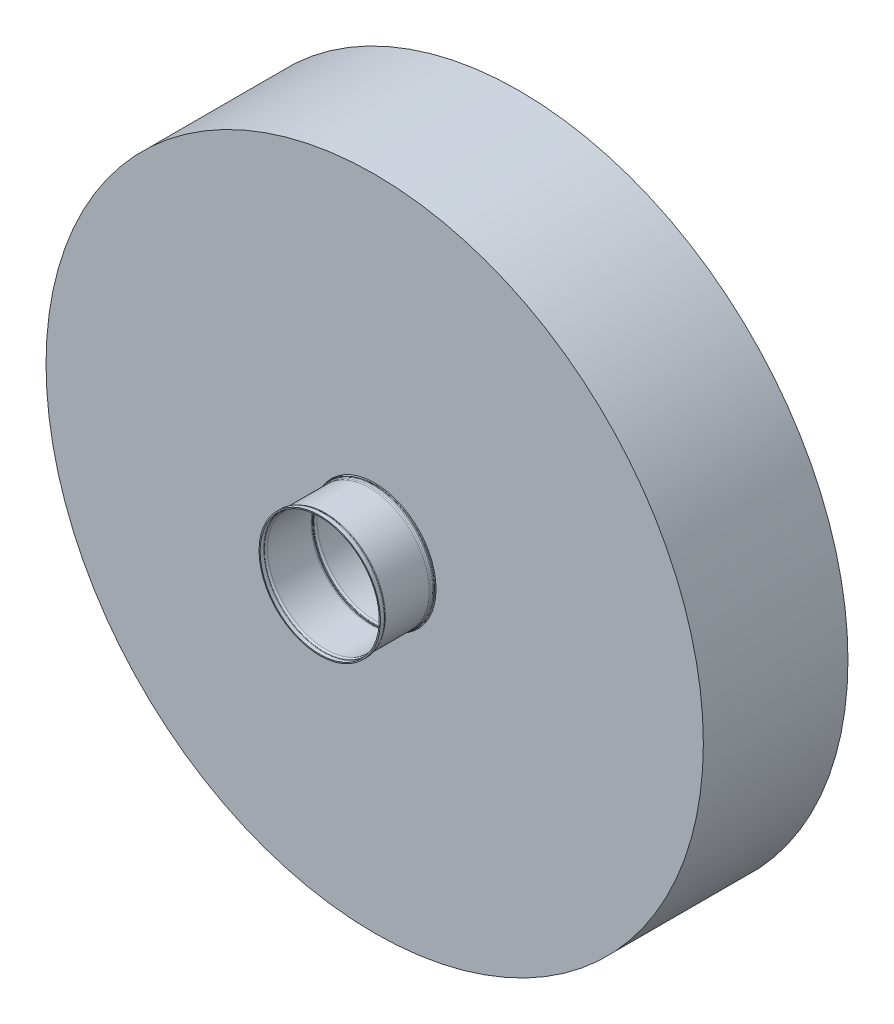
SolidWorks part; units mm, degrees
ref_plane "Front Plane" through (0, 0, 0) normal (0, 0, 1) x (1, 0, 0)
ref_plane "Top Plane" through (0, 0, 0) normal (0, 1, 0) x (1, 0, 0)
ref_plane "Right Plane" through (0, 0, 0) normal (1, 0, 0) x (0, 0, -1)
sketch "Sketch1" plane through (0, 0, 0) normal (0, 0, 1) x (1, 0, 0)
  circle A0 centre (0, 0) radius 28
  circle A1 centre (0, 0) radius 150
extrude "Boss-Extrude1" add sketch "Sketch1" along normal blind 66
sketch "Sketch3" plane through (0, 0, 0) normal (1, 0, 0) x (0, 0, -1)
  line L0 (0, 0) -> (-66, 0) construction
  line L1 (0, -28) -> (0, 28) construction
  line L2 (-66, 28) -> (-66, -28) construction
  line L3 (2.3314, 27.2) -> (22.2571, 27.2)
  line L4 (0, 27.2) -> (-66, 27.2) construction
  line L5 (-91.0885, 27.7) -> (25.0885, 27.7) construction
  line L6 (-91.0885, 27.7) -> (-89.4198, 27.7)
  line L7 (1.7343, 27.4657) -> (1.7657, 27.4343)
  line L8 (-88.8541, 27.4657) -> (-88.8228, 27.4343)
  line L9 (-66.2343, 27.4343) -> (-66.2657, 27.4657)
  line L10 (-33, 0) -> (-33, -3.4567) construction
  line L11 (-66.8314, 27.7) -> (-67.1686, 27.7)
  line L12 (-67.7343, 27.4657) -> (-67.7657, 27.4343)
  line L13 (-91.0885, 27.2) -> (25.0885, 27.2) construction
  line L14 (-65.6686, 27.2) -> (-0.3314, 27.2)
  line L15 (0.8314, 27.7) -> (1.1686, 27.7)
  line L16 (0.2343, 27.4343) -> (0.2657, 27.4657)
  line L17 (22.8541, 27.4657) -> (22.8228, 27.4343)
  line L18 (25.0885, 27.7) -> (23.4198, 27.7)
  line L19 (-91.0885, 27.2) -> (-89.4198, 27.2)
  line L20 (-89.2077, 27.1121) -> (-89.1763, 27.0808)
  line L21 (-88.2571, 26.7) -> (-68.3314, 26.7)
  line L22 (-67.3808, 27.1121) -> (-67.4121, 27.0808)
  line L23 (-66.8314, 27.2) -> (-67.1686, 27.2)
  line L24 (-66.5879, 27.0808) -> (-66.6192, 27.1121)
  line L25 (-65.6686, 26.7) -> (-0.3314, 26.7)
  line L26 (0.5879, 27.0808) -> (0.6192, 27.1121)
  line L27 (0.8314, 27.2) -> (1.1686, 27.2)
  line L28 (1.3808, 27.1121) -> (1.4121, 27.0808)
  line L29 (2.3314, 26.7) -> (22.2571, 26.7)
  line L30 (23.2077, 27.1121) -> (23.1763, 27.0808)
  line L31 (25.0885, 27.2) -> (23.4198, 27.2)
  line L32 (-91.0885, 27.7) -> (-91.0885, 27.2)
  line L33 (25.0885, 27.7) -> (25.0885, 27.2)
  line L43 (-88.2571, 27.2) -> (-68.3314, 27.2)
  arc A0 (22.8541, 27.4657) -> (23.4198, 27.7) centre (23.4198, 26.9) cw
  arc A1 (22.2571, 27.2) -> (22.8228, 27.4343) centre (22.2571, 28) ccw
  arc A2 (0.8314, 27.7) -> (0.2657, 27.4657) centre (0.8314, 26.9) ccw
  arc A3 (1.7343, 27.4657) -> (1.1686, 27.7) centre (1.1686, 26.9) ccw
  arc A4 (0.2343, 27.4343) -> (-0.3314, 27.2) centre (-0.3314, 28) cw
  arc A5 (2.3314, 27.2) -> (1.7657, 27.4343) centre (2.3314, 28) cw
  arc A6 (-67.1686, 27.7) -> (-67.7343, 27.4657) centre (-67.1686, 26.9) ccw
  arc A7 (-66.2657, 27.4657) -> (-66.8314, 27.7) centre (-66.8314, 26.9) ccw
  arc A8 (-67.7657, 27.4343) -> (-68.3314, 27.2) centre (-68.3314, 28) cw
  arc A9 (-66.2343, 27.4343) -> (-65.6686, 27.2) centre (-65.6686, 28) ccw
  arc A10 (-88.8228, 27.4343) -> (-88.2571, 27.2) centre (-88.2571, 28) ccw
  arc A11 (-89.4198, 27.7) -> (-88.8541, 27.4657) centre (-89.4198, 26.9) cw
  arc A12 (-89.4198, 27.2) -> (-89.2077, 27.1121) centre (-89.4198, 26.9) cw
  arc A13 (-89.1763, 27.0808) -> (-88.2571, 26.7) centre (-88.2571, 28) ccw
  arc A14 (-67.4121, 27.0808) -> (-68.3314, 26.7) centre (-68.3314, 28) cw
  arc A15 (-67.1686, 27.2) -> (-67.3808, 27.1121) centre (-67.1686, 26.9) ccw
  arc A16 (-66.6192, 27.1121) -> (-66.8314, 27.2) centre (-66.8314, 26.9) ccw
  arc A17 (-66.5879, 27.0808) -> (-65.6686, 26.7) centre (-65.6686, 28) ccw
  arc A18 (0.5879, 27.0808) -> (-0.3314, 26.7) centre (-0.3314, 28) cw
  arc A19 (0.8314, 27.2) -> (0.6192, 27.1121) centre (0.8314, 26.9) ccw
  arc A20 (1.3808, 27.1121) -> (1.1686, 27.2) centre (1.1686, 26.9) ccw
  arc A21 (2.3314, 26.7) -> (1.4121, 27.0808) centre (2.3314, 28) cw
  arc A22 (22.2571, 26.7) -> (23.1763, 27.0808) centre (22.2571, 28) ccw
  arc A23 (23.2077, 27.1121) -> (23.4198, 27.2) centre (23.4198, 26.9) cw
  point P25 (23.0885, 27.7)
  point P29 (22.5885, 27.2)
  point P32 (0.5, 27.7)
  point P35 (1.5, 27.7)
  point P41 (2, 27.2)
  point P44 (-67.5, 27.7)
  point P47 (-66.5, 27.7)
  point P50 (-68, 27.2)
  point P56 (-88.5885, 27.2)
  point P59 (-89.0885, 27.7)
  dimension "D2" = 27.2
  dimension "D3" = 0.8
  dimension "D1" = 0.5
  dimension "D4" = 0.5
revolve "Revolve1" add sketch "Sketch3" angle 360 about L0
sketch "Sketch5" plane through (0, 0, 0) normal (0, 0, 1) x (1, 0, 0)
  line L0 (-28, 0) -> (-50, 0) construction
  line L1 (0.3052, -37.7766) -> (-0.3052, -37.7766)
  line L2 (28.3267, -69.2412) -> (28.3267, -49.2412) construction
  line L3 (-21.9576, -30.7413) -> (-22.4514, -30.3825)
  line L4 (22.4514, -30.3825) -> (21.9576, -30.7413)
  line L5 (39.6017, -35.6122) -> (39.6017, -64.2412)
  line L6 (-39.6017, -35.6122) -> (-39.6017, -64.2412)
  line L7 (12.0517, -45.1412) -> (12.0517, -49.2412) construction
  line L8 (-12.0517, -45.1412) -> (-12.0517, -49.2412) construction
  line L9 (12.0517, -49.2412) -> (-12.0517, -49.2412)
  line L10 (-17.0517, -54.2412) -> (-17.0517, -64.2412)
  line L11 (17.0517, -54.2412) -> (17.0517, -64.2412)
  line L12 (-22.0517, -69.2412) -> (-34.6017, -69.2412)
  line L13 (22.0517, -69.2412) -> (34.6017, -69.2412)
  line L14 (37.6017, -35.6122) -> (37.6017, -64.2412)
  line L15 (22.0517, -67.2412) -> (34.6017, -67.2412)
  line L16 (19.0517, -54.2412) -> (19.0517, -64.2412)
  line L17 (12.0517, -47.2412) -> (-12.0517, -47.2412)
  line L18 (-19.0517, -54.2412) -> (-19.0517, -64.2412)
  line L19 (-22.0517, -67.2412) -> (-34.6017, -67.2412)
  line L20 (-37.6017, -35.6122) -> (-37.6017, -64.2412)
  line L21 (-23.1332, -32.3593) -> (-23.627, -32.0005)
  line L22 (0.3052, -39.7766) -> (-0.3052, -39.7766)
  line L23 (23.627, -32.0005) -> (23.1332, -32.3593)
  line L24 (-28.3267, -69.2412) -> (-28.3267, -49.2412) construction
  line L25 (19.1517, -46.4507) -> (19.1517, -64.2412)
  line L26 (22.0517, -67.1412) -> (26.2767, -67.1412)
  line L27 (28.3767, -53.9226) -> (28.3767, -52.2412)
  line L28 (28.3767, -65.1412) -> (28.3767, -64.5598)
  line L29 (28.2767, -53.9226) -> (28.2767, -52.2412)
  line L30 (34.6017, -67.1412) -> (30.3767, -67.1412)
  line L31 (37.5017, -54.2412) -> (37.5017, -64.2412)
  line L33 (28.2767, -65.1412) -> (28.2767, -64.5598)
  line L35 (27.9406, -50.8616) -> (23.8467, -42.956)
  line L36 (31.3767, -49.2412) -> (32.5017, -49.2412)
  line L38 (26.1647, -51.7814) -> (22.0707, -43.8757)
  line L39 (21.1517, -46.4507) -> (21.1517, -64.2412)
  line L40 (22.0517, -65.1412) -> (26.2767, -65.1412)
  line L41 (26.2767, -65.1412) -> (26.2767, -64.5598)
  line L42 (26.2767, -53.9226) -> (26.2767, -52.2412)
  line L43 (31.3767, -51.2412) -> (32.5017, -51.2412)
  line L44 (35.5017, -54.2412) -> (35.5017, -64.2412)
  line L45 (34.6017, -65.1412) -> (30.3767, -65.1412)
  line L46 (30.3767, -65.1412) -> (30.3767, -64.5598)
  line L47 (30.3767, -53.9226) -> (30.3767, -52.2412)
  line L48 (0, -49.2412) -> (0, -54.6682) construction
  line L49 (-31.3767, -49.2412) -> (-32.5017, -49.2412)
  line L50 (-28.3767, -53.9226) -> (-28.3767, -52.2412)
  line L51 (-28.3767, -65.1412) -> (-28.3767, -64.5598)
  line L52 (-34.6017, -67.1412) -> (-30.3767, -67.1412)
  line L53 (-37.5017, -54.2412) -> (-37.5017, -64.2412)
  line L54 (-31.3767, -51.2412) -> (-32.5017, -51.2412)
  line L55 (-30.3767, -53.9226) -> (-30.3767, -52.2412)
  line L56 (-30.3767, -65.1412) -> (-30.3767, -64.5598)
  line L57 (-34.6017, -65.1412) -> (-30.3767, -65.1412)
  line L58 (-35.5017, -54.2412) -> (-35.5017, -64.2412)
  line L59 (-26.1647, -51.7814) -> (-22.0707, -43.8757)
  line L60 (-26.2767, -53.9226) -> (-26.2767, -52.2412)
  line L61 (-26.2767, -65.1412) -> (-26.2767, -64.5598)
  line L62 (-22.0517, -65.1412) -> (-26.2767, -65.1412)
  line L63 (-21.1517, -46.4507) -> (-21.1517, -64.2412)
  line L64 (-27.9406, -50.8616) -> (-23.8467, -42.956)
  line L65 (-28.2767, -53.9226) -> (-28.2767, -52.2412)
  line L66 (-28.2767, -65.1412) -> (-28.2767, -64.5598)
  line L67 (-22.0517, -67.1412) -> (-26.2767, -67.1412)
  line L68 (-19.1517, -46.4507) -> (-19.1517, -64.2412)
  arc A0 (25.5034, -28.1599) -> (23.5717, -23.4899) centre (31.5517, -22.9236) ccw
  circle A1 centre (0, 0) radius 24.2 construction
  arc A2 (15.0561, -29.6768) -> (5.2629, -32.8588) centre (12.0517, -37.0912) ccw
  circle A3 centre (-39, 0) radius 11 construction
  circle A4 centre (-31.5517, 22.9236) radius 11 construction
  circle A5 centre (-12.0517, 37.0912) radius 11 construction
  circle A6 centre (12.0517, 37.0912) radius 11 construction
  circle A7 centre (31.5517, 22.9236) radius 11 construction
  circle A8 centre (39, 0) radius 11 construction
  circle A9 centre (31.5517, -22.9236) radius 11 construction
  circle A10 centre (12.0517, -37.0912) radius 11 construction
  circle A11 centre (-12.0517, -37.0912) radius 11 construction
  circle A12 centre (-31.5517, -22.9236) radius 11 construction
  circle A13 centre (31.5517, -22.9236) radius 4
  circle A14 centre (12.0517, -37.0912) radius 4
  circle A15 centre (-12.0517, -37.0912) radius 4
  circle A16 centre (-31.5517, -22.9236) radius 4
  arc A17 (-5.2629, -32.8588) -> (-15.0561, -29.6768) centre (-12.0517, -37.0912) ccw
  arc A18 (-23.5717, -23.4899) -> (-25.5034, -28.1599) centre (-31.5517, -22.9236) ccw
  arc A19 (-22.7286, -27.9179) -> (-19.528, -30.2433) centre (0, 0) ccw
  arc A20 (-22.9253, -25.1084) -> (-16.7952, -29.5622) centre (0, 0) ccw
  arc A21 (4.8058, -40.5983) -> (19.9751, -35.6695) centre (12.0517, -37.0912) ccw
  arc A22 (-19.9751, -35.6695) -> (-4.8058, -40.5983) centre (-12.0517, -37.0912) ccw
  arc A23 (-33.4331, -30.7507) -> (-27.751, -30.0199) centre (-31.5517, -22.9236) ccw
  arc A24 (19.528, -30.2433) -> (22.7286, -27.9179) centre (0, 0) ccw
  arc A25 (4.0807, -37.7723) -> (18.9006, -32.957) centre (12.0517, -37.0912) ccw
  arc A26 (16.7952, -29.5622) -> (22.9253, -25.1084) centre (0, 0) ccw
  arc A27 (27.751, -30.0199) -> (33.4331, -30.7507) centre (31.5517, -22.9236) ccw
  arc A28 (-3.7886, -33.7883) -> (3.7886, -33.7883) centre (0, 0) ccw
  arc A29 (-1.9781, -35.9456) -> (1.9781, -35.9456) centre (0, 0) ccw
  arc A31 (-18.9006, -32.957) -> (-4.0807, -37.7723) centre (-12.0517, -37.0912) ccw
  arc A32 (-27.751, -30.0199) -> (-22.4514, -30.3825) centre (-25.3904, -34.4276) cw
  arc A33 (-22.7286, -27.9179) -> (-25.5034, -28.1599) centre (-23.9913, -29.4689) ccw
  arc A34 (-22.9253, -25.1084) -> (-23.5717, -23.4899) centre (-21.5767, -23.6314) cw
  arc A35 (-18.9006, -32.957) -> (-19.528, -30.2433) centre (-20.6129, -31.9235) ccw
  arc A36 (-16.7952, -29.5622) -> (-15.0561, -29.6768) centre (-15.8072, -27.8232) ccw
  arc A37 (-1.9781, -35.9456) -> (-4.0807, -37.7723) centre (-2.088, -37.9426) ccw
  arc A38 (-3.7886, -33.7883) -> (-5.2629, -32.8588) centre (-3.5657, -31.8007) cw
  arc A39 (4.0807, -37.7723) -> (1.9781, -35.9456) centre (2.088, -37.9426) ccw
  arc A40 (5.2629, -32.8588) -> (3.7886, -33.7883) centre (3.5657, -31.8007) cw
  arc A41 (15.0561, -29.6768) -> (16.7952, -29.5622) centre (15.8072, -27.8232) ccw
  arc A42 (18.9006, -32.957) -> (19.528, -30.2433) centre (20.6129, -31.9235) cw
  arc A43 (22.7286, -27.9179) -> (25.5034, -28.1599) centre (23.9913, -29.4689) cw
  arc A44 (23.5717, -23.4899) -> (22.9253, -25.1084) centre (21.5767, -23.6314) cw
  arc A46 (-19.9751, -35.6695) -> (-21.9576, -30.7413) centre (-24.8965, -34.7864) ccw
  arc A47 (-4.8058, -40.5983) -> (-0.3052, -37.7766) centre (-0.3052, -42.7766) cw
  arc A49 (4.8058, -40.5983) -> (0.3052, -37.7766) centre (0.3052, -42.7766) ccw
  arc A50 (19.9751, -35.6695) -> (21.9576, -30.7413) centre (24.8965, -34.7864) cw
  arc A52 (27.751, -30.0199) -> (22.4514, -30.3825) centre (25.3904, -34.4276) ccw
  arc A53 (-39.6017, -35.6122) -> (-33.4331, -30.7507) centre (-34.6017, -35.6122) cw
  arc A54 (39.6017, -35.6122) -> (33.4331, -30.7507) centre (34.6017, -35.6122) ccw
  arc A55 (12.0517, -49.2412) -> (17.0517, -54.2412) centre (12.0517, -54.2412) cw
  arc A56 (-12.0517, -49.2412) -> (-17.0517, -54.2412) centre (-12.0517, -54.2412) ccw
  arc A57 (34.6017, -69.2412) -> (39.6017, -64.2412) centre (34.6017, -64.2412) ccw
  arc A58 (-34.6017, -69.2412) -> (-39.6017, -64.2412) centre (-34.6017, -64.2412) cw
  arc A59 (-22.0517, -69.2412) -> (-17.0517, -64.2412) centre (-22.0517, -64.2412) ccw
  arc A60 (17.0517, -64.2412) -> (22.0517, -69.2412) centre (22.0517, -64.2412) ccw
  arc A61 (34.6017, -67.2412) -> (37.6017, -64.2412) centre (34.6017, -64.2412) ccw
  arc A62 (19.0517, -64.2412) -> (22.0517, -67.2412) centre (22.0517, -64.2412) ccw
  arc A63 (12.0517, -47.2412) -> (19.0517, -54.2412) centre (12.0517, -54.2412) cw
  arc A64 (-12.0517, -47.2412) -> (-19.0517, -54.2412) centre (-12.0517, -54.2412) ccw
  arc A65 (-22.0517, -67.2412) -> (-19.0517, -64.2412) centre (-22.0517, -64.2412) ccw
  arc A66 (-34.6017, -67.2412) -> (-37.6017, -64.2412) centre (-34.6017, -64.2412) cw
  arc A67 (-37.6017, -35.6122) -> (-33.9005, -32.6953) centre (-34.6017, -35.6122) cw
  arc A68 (-33.9005, -32.6953) -> (-26.8068, -31.783) centre (-31.5517, -22.9236) ccw
  arc A69 (-26.8068, -31.783) -> (-23.627, -32.0005) centre (-25.3904, -34.4276) cw
  arc A70 (-21.9437, -35.3162) -> (-23.1332, -32.3593) centre (-24.8965, -34.7864) ccw
  arc A71 (-21.9437, -35.3162) -> (-3.0055, -41.4696) centre (-12.0517, -37.0912) ccw
  arc A72 (-3.0055, -41.4696) -> (-0.3052, -39.7766) centre (-0.3052, -42.7766) cw
  arc A73 (3.0055, -41.4696) -> (0.3052, -39.7766) centre (0.3052, -42.7766) ccw
  arc A74 (3.0055, -41.4696) -> (21.9437, -35.3162) centre (12.0517, -37.0912) ccw
  arc A75 (21.9437, -35.3162) -> (23.1332, -32.3593) centre (24.8965, -34.7864) cw
  arc A76 (26.8068, -31.783) -> (23.627, -32.0005) centre (25.3904, -34.4276) ccw
  arc A77 (26.8068, -31.783) -> (33.9005, -32.6953) centre (31.5517, -22.9236) ccw
  arc A78 (37.6017, -35.6122) -> (33.9005, -32.6953) centre (34.6017, -35.6122) ccw
  circle A79 centre (28.3267, -59.2412) radius 1.6
  circle A80 centre (-28.3267, -59.2412) radius 1.6
  circle A81 centre (28.3267, -59.2412) radius 3.6
  circle A82 centre (-28.3267, -59.2412) radius 3.6
  arc A83 (19.1517, -64.2412) -> (22.0517, -67.1412) centre (22.0517, -64.2412) ccw
  arc A84 (29.6574, -55.7888) -> (28.3767, -53.9226) centre (30.3767, -53.9226) cw
  arc A85 (26.996, -55.7888) -> (26.996, -62.6936) centre (28.3267, -59.2412) ccw
  arc A87 (28.2767, -64.5598) -> (26.996, -62.6936) centre (26.2767, -64.5598) ccw
  arc A88 (26.996, -55.7888) -> (28.2767, -53.9226) centre (26.2767, -53.9226) ccw
  arc A89 (26.2767, -67.1412) -> (28.2767, -65.1412) centre (26.2767, -65.1412) ccw
  arc A91 (29.6574, -55.7888) -> (29.6574, -62.6936) centre (28.3267, -59.2412) cw
  arc A92 (28.3767, -64.5598) -> (29.6574, -62.6936) centre (30.3767, -64.5598) cw
  arc A93 (30.3767, -67.1412) -> (28.3767, -65.1412) centre (30.3767, -65.1412) cw
  arc A94 (37.5017, -64.2412) -> (34.6017, -67.1412) centre (34.6017, -64.2412) cw
  arc A95 (32.5017, -49.2412) -> (37.5017, -54.2412) centre (32.5017, -54.2412) cw
  arc A96 (20.2697, -42.9627) -> (20.4146, -42.7543) centre (12.0517, -37.0912) ccw
  arc A97 (27.9406, -50.8616) -> (28.2767, -52.2412) centre (25.2767, -52.2412) cw
  arc A98 (28.3767, -52.2412) -> (31.3767, -49.2412) centre (31.3767, -52.2412) cw
  arc A99 (19.1517, -46.4507) -> (20.2697, -42.9627) centre (25.1517, -46.4507) cw
  arc A100 (23.8467, -42.956) -> (20.4146, -42.7543) centre (22.0707, -43.8757) ccw
  arc A102 (21.897, -44.1254) -> (22.0707, -43.8757) centre (12.0517, -37.0912) ccw
  arc A103 (21.1517, -46.4507) -> (21.897, -44.1254) centre (25.1517, -46.4507) cw
  arc A104 (21.1517, -64.2412) -> (22.0517, -65.1412) centre (22.0517, -64.2412) ccw
  arc A107 (26.2767, -53.9226) -> (26.2767, -64.5598) centre (28.3267, -59.2412) ccw
  arc A109 (26.1647, -51.7814) -> (26.2767, -52.2412) centre (25.2767, -52.2412) cw
  arc A110 (30.3767, -52.2412) -> (31.3767, -51.2412) centre (31.3767, -52.2412) cw
  arc A111 (32.5017, -51.2412) -> (35.5017, -54.2412) centre (32.5017, -54.2412) cw
  arc A112 (35.5017, -64.2412) -> (34.6017, -65.1412) centre (34.6017, -64.2412) cw
  arc A115 (30.3767, -53.9226) -> (30.3767, -64.5598) centre (28.3267, -59.2412) cw
  arc A117 (-28.3767, -52.2412) -> (-31.3767, -49.2412) centre (-31.3767, -52.2412) ccw
  arc A118 (-29.6574, -55.7888) -> (-28.3767, -53.9226) centre (-30.3767, -53.9226) ccw
  arc A119 (-29.6574, -55.7888) -> (-29.6574, -62.6936) centre (-28.3267, -59.2412) ccw
  arc A120 (-28.3767, -64.5598) -> (-29.6574, -62.6936) centre (-30.3767, -64.5598) ccw
  arc A121 (-30.3767, -67.1412) -> (-28.3767, -65.1412) centre (-30.3767, -65.1412) ccw
  arc A122 (-37.5017, -64.2412) -> (-34.6017, -67.1412) centre (-34.6017, -64.2412) ccw
  arc A123 (-32.5017, -49.2412) -> (-37.5017, -54.2412) centre (-32.5017, -54.2412) ccw
  arc A124 (-30.3767, -52.2412) -> (-31.3767, -51.2412) centre (-31.3767, -52.2412) ccw
  arc A125 (-30.3767, -53.9226) -> (-30.3767, -64.5598) centre (-28.3267, -59.2412) ccw
  arc A126 (-35.5017, -64.2412) -> (-34.6017, -65.1412) centre (-34.6017, -64.2412) ccw
  arc A127 (-32.5017, -51.2412) -> (-35.5017, -54.2412) centre (-32.5017, -54.2412) ccw
  arc A128 (-21.1517, -46.4507) -> (-21.897, -44.1254) centre (-25.1517, -46.4507) ccw
  arc A129 (-21.897, -44.1254) -> (-22.0707, -43.8757) centre (-12.0517, -37.0912) cw
  arc A130 (-26.1647, -51.7814) -> (-26.2767, -52.2412) centre (-25.2767, -52.2412) ccw
  arc A131 (-26.2767, -53.9226) -> (-26.2767, -64.5598) centre (-28.3267, -59.2412) cw
  arc A132 (-21.1517, -64.2412) -> (-22.0517, -65.1412) centre (-22.0517, -64.2412) cw
  arc A133 (-19.1517, -46.4507) -> (-20.2697, -42.9627) centre (-25.1517, -46.4507) ccw
  arc A134 (-20.2697, -42.9627) -> (-20.4146, -42.7543) centre (-12.0517, -37.0912) cw
  arc A135 (-23.8467, -42.956) -> (-20.4146, -42.7543) centre (-22.0707, -43.8757) cw
  arc A136 (-27.9406, -50.8616) -> (-28.2767, -52.2412) centre (-25.2767, -52.2412) ccw
  arc A137 (-26.996, -55.7888) -> (-28.2767, -53.9226) centre (-26.2767, -53.9226) cw
  arc A138 (-26.996, -55.7888) -> (-26.996, -62.6936) centre (-28.3267, -59.2412) cw
  arc A139 (-28.2767, -64.5598) -> (-26.996, -62.6936) centre (-26.2767, -64.5598) cw
  arc A140 (-26.2767, -67.1412) -> (-28.2767, -65.1412) centre (-26.2767, -65.1412) cw
  arc A141 (-19.1517, -64.2412) -> (-22.0517, -67.1412) centre (-22.0517, -64.2412) cw
  point P32 (0, 0)
  point P63 (-6.2036, -42.5502)
  point P70 (19.9915, -38.0702)
  point P73 (15.8772, -30.0652)
  point P76 (-8.3998, -44.2091)
  point P77 (17.65, -31.3764)
  point P79 (-5.47, -32.5435)
  point P81 (16.84, -30.6825)
  point P116 (-39.6017, -22.9236)
  point P118 (14.7033, -29.5434)
  point P120 (39.6017, -22.9236)
  point P121 (19.1898, -40.7032)
  point P215 (28.2767, -55.5415)
  point P237 (28.2767, -49.2412)
  point P240 (28.3767, -49.2412)
extrude "Boss-Extrude4" add sketch "Sketch5" against normal blind 4 from offset 4 separate body contours L11 A60 L13 A57 L5 A54 A27 A52 L4 A50 A21 A49 L1 A47 A22 A46 L3 A32 A23 A53 L6 A58 L12 A59 L10 A56 L9 A55 A78 L14 A61 L15 A62 L16 A63 L17 A64 L18 A65 L19 A66 L20 A67 A68 A69 L21 A70 A71 A72 L22 | A0 A44 A26 A41 A2 A40 A28 A38 A17 A36 A20 A34 A18 A33 A19 A35 A31 A37 A29 A39 A25 A42 A24 A43 A13 A14 A15 A16 | L35 A100 A96 A99 L25 A83 L26 A89 L33 A87 A85 A88 L29 A97 L38 A109 L42 A107 L41 L40 A104 L39 A103 A102 | A98 L27 A84 A91 A92 L28 A93 L30 A94 L31 A95 L36 A115 L47 A110 L43 A111 L44 A112 L45 L46 | A141 L68 A133 A134 A135 L64 A136 L65 A137 A138 A139 L66 A140 L67 L63 A132 L62 L61 A131 L60 A130 L59 A129 A128 | L49 A123 L53 A122 L52 A121 L51 A120 A119 A118 L50 A117 A127 L54 A124 L55 A125 L56 L57 A126 L58 | A81 A79 | A82 A80 offset against normal yes
sketch "Sketch6" plane through (0, 0, -8) normal (0, 0, -1) x (-1, 0, 0)
  line L0 (-36.6017, -49.2412) -> (36.6017, -49.2412)
  line L1 (-39.6017, -35.6122) -> (-39.6017, -64.2412) construction
  line L2 (21.9576, -30.7413) -> (22.4514, -30.3825) construction
  line L3 (-39.6017, -35.6636) -> (-39.6017, -46.2412)
  line L4 (39.6017, -35.6122) -> (39.6017, -64.2412) construction
  line L5 (39.6017, -35.6636) -> (39.6017, -46.2412)
  line L6 (-0.3052, -37.7766) -> (0.3052, -37.7766) construction
  line L7 (-22.4514, -30.3825) -> (-21.9576, -30.7413) construction
  line L8 (21.9576, -30.7413) -> (22.4514, -30.3825)
  line L9 (-0.3052, -37.7766) -> (0.3052, -37.7766)
  line L10 (-22.4514, -30.3825) -> (-21.9576, -30.7413)
  line L11 (-23.627, -32.0005) -> (-23.1332, -32.3593)
  line L12 (-0.3052, -39.7766) -> (0.3052, -39.7766)
  line L13 (23.1332, -32.3593) -> (23.627, -32.0005)
  line L14 (37.6017, -35.6636) -> (37.6017, -46.2412)
  line L15 (-36.6017, -47.2412) -> (36.6017, -47.2412)
  line L16 (-37.6017, -35.6636) -> (-37.6017, -46.2412)
  circle A0 centre (31.5517, -22.9236) radius 4 construction
  circle A1 centre (12.0517, -37.0912) radius 4 construction
  circle A2 centre (-31.5517, -22.9236) radius 4 construction
  circle A3 centre (-12.0517, -37.0912) radius 4 construction
  circle A4 centre (31.5517, -22.9236) radius 4
  circle A5 centre (12.0517, -37.0912) radius 4
  circle A6 centre (-31.5517, -22.9236) radius 4
  circle A7 centre (-12.0517, -37.0912) radius 4
  arc A8 (-33.4375, -30.801) -> (-27.2468, -29.785) centre (-31.5517, -22.9236) ccw
  arc A9 (-37.6017, -35.6636) -> (-33.9032, -32.7461) centre (-34.6017, -35.6636) cw
  arc A10 (-33.9032, -32.7461) -> (-26.3657, -31.5905) centre (-31.5517, -22.9236) ccw
  arc A11 (-23.627, -32.0005) -> (-26.3657, -31.5905) centre (-25.3904, -34.4276) ccw
  arc A12 (-19.9075, -35.1174) -> (-4.536, -40.1119) centre (-12.0517, -37.0912) ccw
  arc A13 (-21.8969, -34.8372) -> (-23.1332, -32.3593) centre (-24.8965, -34.7864) ccw
  arc A14 (-21.8969, -34.8372) -> (-2.7618, -41.0546) centre (-12.0517, -37.0912) ccw
  arc A15 (-0.3052, -39.7766) -> (-2.7618, -41.0546) centre (-0.3052, -42.7766) ccw
  arc A16 (4.536, -40.1119) -> (19.9075, -35.1174) centre (12.0517, -37.0912) ccw
  arc A17 (2.7618, -41.0546) -> (0.3052, -39.7766) centre (0.3052, -42.7766) ccw
  arc A18 (2.7618, -41.0546) -> (21.8969, -34.8372) centre (12.0517, -37.0912) ccw
  arc A19 (23.1332, -32.3593) -> (21.8969, -34.8372) centre (24.8965, -34.7864) ccw
  arc A20 (27.2468, -29.785) -> (33.4375, -30.801) centre (31.5517, -22.9236) ccw
  arc A21 (-39.6017, -35.6636) -> (-33.4375, -30.801) centre (-34.6017, -35.6636) cw
  arc A22 (39.6017, -35.6636) -> (33.4375, -30.801) centre (34.6017, -35.6636) ccw
  arc A23 (36.6017, -49.2412) -> (39.6017, -46.2412) centre (36.6017, -46.2412) ccw
  arc A24 (-23.5717, -23.4899) -> (-25.5034, -28.1599) centre (-31.5517, -22.9236) ccw
  arc A25 (-22.7286, -27.9179) -> (-25.5034, -28.1599) centre (-23.9913, -29.4689) ccw
  arc A26 (-22.7286, -27.9179) -> (-19.528, -30.2433) centre (0, 0) ccw
  arc A27 (-18.9006, -32.957) -> (-19.528, -30.2433) centre (-20.6129, -31.9235) ccw
  arc A28 (-18.9006, -32.957) -> (-4.0807, -37.7723) centre (-12.0517, -37.0912) ccw
  arc A29 (-1.9781, -35.9456) -> (-4.0807, -37.7723) centre (-2.088, -37.9426) ccw
  arc A30 (-1.9781, -35.9456) -> (1.9781, -35.9456) centre (0, 0) ccw
  arc A31 (4.0807, -37.7723) -> (1.9781, -35.9456) centre (2.088, -37.9426) ccw
  arc A32 (4.0807, -37.7723) -> (18.9006, -32.957) centre (12.0517, -37.0912) ccw
  arc A33 (19.528, -30.2433) -> (18.9006, -32.957) centre (20.6129, -31.9235) ccw
  arc A34 (19.528, -30.2433) -> (22.7286, -27.9179) centre (0, 0) ccw
  arc A35 (25.5034, -28.1599) -> (22.7286, -27.9179) centre (23.9913, -29.4689) ccw
  arc A36 (25.5034, -28.1599) -> (23.5717, -23.4899) centre (31.5517, -22.9236) ccw
  arc A37 (22.9253, -25.1084) -> (23.5717, -23.4899) centre (21.5767, -23.6314) ccw
  arc A38 (16.7952, -29.5622) -> (22.9253, -25.1084) centre (0, 0) ccw
  arc A39 (15.0561, -29.6768) -> (16.7952, -29.5622) centre (15.8072, -27.8232) ccw
  arc A40 (15.0561, -29.6768) -> (5.2629, -32.8588) centre (12.0517, -37.0912) ccw
  arc A41 (3.7886, -33.7883) -> (5.2629, -32.8588) centre (3.5657, -31.8007) ccw
  arc A42 (-3.7886, -33.7883) -> (3.7886, -33.7883) centre (0, 0) ccw
  arc A43 (-5.2629, -32.8588) -> (-3.7886, -33.7883) centre (-3.5657, -31.8007) ccw
  arc A44 (-5.2629, -32.8588) -> (-15.0561, -29.6768) centre (-12.0517, -37.0912) ccw
  arc A45 (-16.7952, -29.5622) -> (-15.0561, -29.6768) centre (-15.8072, -27.8232) ccw
  arc A46 (-22.9253, -25.1084) -> (-16.7952, -29.5622) centre (0, 0) ccw
  arc A47 (-23.5717, -23.4899) -> (-22.9253, -25.1084) centre (-21.5767, -23.6314) ccw
  arc A48 (-23.5717, -23.4899) -> (-25.5034, -28.1599) centre (-31.5517, -22.9236) ccw
  arc A49 (-22.7286, -27.9179) -> (-25.5034, -28.1599) centre (-23.9913, -29.4689) ccw
  arc A50 (-22.7286, -27.9179) -> (-19.528, -30.2433) centre (0, 0) ccw
  arc A51 (-18.9006, -32.957) -> (-19.528, -30.2433) centre (-20.6129, -31.9235) ccw
  arc A52 (-18.9006, -32.957) -> (-4.0807, -37.7723) centre (-12.0517, -37.0912) ccw
  arc A53 (-1.9781, -35.9456) -> (-4.0807, -37.7723) centre (-2.088, -37.9426) ccw
  arc A54 (-1.9781, -35.9456) -> (1.9781, -35.9456) centre (0, 0) ccw
  arc A55 (4.0807, -37.7723) -> (1.9781, -35.9456) centre (2.088, -37.9426) ccw
  arc A56 (4.0807, -37.7723) -> (18.9006, -32.957) centre (12.0517, -37.0912) ccw
  arc A57 (19.528, -30.2433) -> (18.9006, -32.957) centre (20.6129, -31.9235) ccw
  arc A58 (19.528, -30.2433) -> (22.7286, -27.9179) centre (0, 0) ccw
  arc A59 (25.5034, -28.1599) -> (22.7286, -27.9179) centre (23.9913, -29.4689) ccw
  arc A60 (25.5034, -28.1599) -> (23.5717, -23.4899) centre (31.5517, -22.9236) ccw
  arc A61 (22.9253, -25.1084) -> (23.5717, -23.4899) centre (21.5767, -23.6314) ccw
  arc A62 (16.7952, -29.5622) -> (22.9253, -25.1084) centre (0, 0) ccw
  arc A63 (15.0561, -29.6768) -> (16.7952, -29.5622) centre (15.8072, -27.8232) ccw
  arc A64 (15.0561, -29.6768) -> (5.2629, -32.8588) centre (12.0517, -37.0912) ccw
  arc A65 (3.7886, -33.7883) -> (5.2629, -32.8588) centre (3.5657, -31.8007) ccw
  arc A66 (-3.7886, -33.7883) -> (3.7886, -33.7883) centre (0, 0) ccw
  arc A67 (-5.2629, -32.8588) -> (-3.7886, -33.7883) centre (-3.5657, -31.8007) ccw
  arc A68 (-5.2629, -32.8588) -> (-15.0561, -29.6768) centre (-12.0517, -37.0912) ccw
  arc A69 (-16.7952, -29.5622) -> (-15.0561, -29.6768) centre (-15.8072, -27.8232) ccw
  arc A70 (-22.9253, -25.1084) -> (-16.7952, -29.5622) centre (0, 0) ccw
  arc A71 (-23.5717, -23.4899) -> (-22.9253, -25.1084) centre (-21.5767, -23.6314) ccw
  arc A72 (-36.6017, -49.2412) -> (-39.6017, -46.2412) centre (-36.6017, -46.2412) cw
  arc A73 (27.751, -30.0199) -> (22.4514, -30.3825) centre (25.3904, -34.4276) ccw construction
  arc A74 (21.9576, -30.7413) -> (19.9751, -35.6695) centre (24.8965, -34.7864) ccw construction
  arc A75 (4.8058, -40.5983) -> (0.3052, -37.7766) centre (0.3052, -42.7766) ccw construction
  arc A76 (-0.3052, -37.7766) -> (-4.8058, -40.5983) centre (-0.3052, -42.7766) ccw construction
  arc A77 (-19.9751, -35.6695) -> (-21.9576, -30.7413) centre (-24.8965, -34.7864) ccw construction
  arc A78 (-22.4514, -30.3825) -> (-27.751, -30.0199) centre (-25.3904, -34.4276) ccw construction
  arc A79 (27.2468, -29.785) -> (22.4514, -30.3825) centre (25.3904, -34.4276) ccw
  arc A80 (-23.472, -23.4969) -> (-25.4278, -28.2253) centre (-31.5517, -22.9236) ccw construction
  arc A81 (25.4278, -28.2253) -> (23.472, -23.4969) centre (31.5517, -22.9236) ccw construction
  arc A82 (-23.472, -23.4969) -> (-22.8579, -25.0345) centre (-21.5767, -23.6314) ccw construction
  arc A83 (-22.8579, -25.0345) -> (-16.7458, -29.4752) centre (0, 0) ccw construction
  arc A84 (-16.7458, -29.4752) -> (-15.0937, -29.5841) centre (-15.8072, -27.8232) ccw construction
  arc A85 (-5.1781, -32.8059) -> (-15.0937, -29.5841) centre (-12.0517, -37.0912) ccw construction
  arc A86 (-5.1781, -32.8059) -> (-3.7775, -33.6889) centre (-3.5657, -31.8007) ccw construction
  arc A87 (-3.7775, -33.6889) -> (3.7775, -33.6889) centre (0, 0) ccw construction
  arc A88 (3.7775, -33.6889) -> (5.1781, -32.8059) centre (3.5657, -31.8007) ccw construction
  arc A89 (15.0937, -29.5841) -> (5.1781, -32.8059) centre (12.0517, -37.0912) ccw construction
  arc A90 (15.0937, -29.5841) -> (16.7458, -29.4752) centre (15.8072, -27.8232) ccw construction
  arc A91 (16.7458, -29.4752) -> (22.8579, -25.0345) centre (0, 0) ccw construction
  arc A92 (22.8579, -25.0345) -> (23.472, -23.4969) centre (21.5767, -23.6314) ccw construction
  arc A93 (21.9576, -30.7413) -> (19.9075, -35.1174) centre (24.8965, -34.7864) ccw
  arc A94 (4.536, -40.1119) -> (0.3052, -37.7766) centre (0.3052, -42.7766) ccw
  arc A95 (-0.3052, -37.7766) -> (-4.536, -40.1119) centre (-0.3052, -42.7766) ccw
  arc A96 (-19.9075, -35.1174) -> (-21.9576, -30.7413) centre (-24.8965, -34.7864) ccw
  arc A97 (-22.4514, -30.3825) -> (-27.2468, -29.785) centre (-25.3904, -34.4276) ccw
  arc A98 (3.9811, -37.7808) -> (18.9863, -32.9053) centre (12.0517, -37.0912) ccw construction
  arc A99 (-18.9863, -32.9053) -> (-3.9811, -37.7808) centre (-12.0517, -37.0912) ccw construction
  arc A100 (-18.9863, -32.9053) -> (-19.5822, -30.3273) centre (-20.6129, -31.9235) ccw construction
  arc A101 (-22.7917, -27.9955) -> (-19.5822, -30.3273) centre (0, 0) ccw construction
  arc A102 (-22.7917, -27.9955) -> (-25.4278, -28.2253) centre (-23.9913, -29.4689) ccw construction
  arc A103 (3.9811, -37.7808) -> (1.9836, -36.0455) centre (2.088, -37.9426) ccw construction
  arc A104 (-1.9836, -36.0455) -> (1.9836, -36.0455) centre (0, 0) ccw construction
  arc A105 (-1.9836, -36.0455) -> (-3.9811, -37.7808) centre (-2.088, -37.9426) ccw construction
  arc A106 (25.4278, -28.2253) -> (22.7917, -27.9955) centre (23.9913, -29.4689) ccw construction
  arc A107 (19.5822, -30.3273) -> (22.7917, -27.9955) centre (0, 0) ccw construction
  arc A108 (19.5822, -30.3273) -> (18.9863, -32.9053) centre (20.6129, -31.9235) ccw construction
  arc A109 (26.3657, -31.5905) -> (23.627, -32.0005) centre (25.3904, -34.4276) ccw
  arc A110 (26.3657, -31.5905) -> (33.9032, -32.7461) centre (31.5517, -22.9236) ccw
  arc A111 (37.6017, -35.6636) -> (33.9032, -32.7461) centre (34.6017, -35.6636) ccw
  arc A112 (36.6017, -47.2412) -> (37.6017, -46.2412) centre (36.6017, -46.2412) ccw
  arc A113 (-36.6017, -47.2412) -> (-37.6017, -46.2412) centre (-36.6017, -46.2412) cw
  dimension "D3" = 5
  dimension "D4" = 3
  dimension "D2" = 0.1
  dimension "D1" = 0
  dimension "D5" = 2
extrude "Boss-Extrude5" add sketch "Sketch6" along normal blind 4
sketch "Sketch7" plane through (0, 0, -12) normal (0, 0, -1) x (-1, 0, 0)
  circle A0 centre (-31.5517, -22.9236) radius 4
  circle A1 centre (-12.0517, -37.0912) radius 4
  circle A2 centre (12.0517, -37.0912) radius 4
  circle A3 centre (31.5517, -22.9236) radius 4
  circle A4 centre (31.5517, -22.9236) radius 6
  circle A5 centre (12.0517, -37.0912) radius 6
  circle A6 centre (-12.0517, -37.0912) radius 6
  circle A7 centre (-31.5517, -22.9236) radius 6
  dimension "D1" = 2
